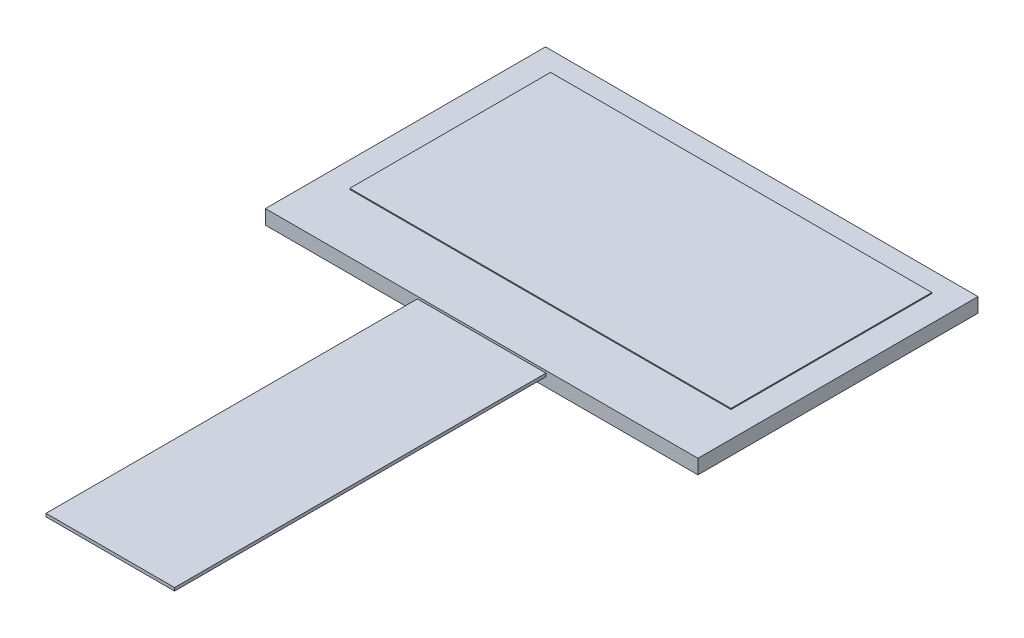
SolidWorks part; units mm, degrees
ref_plane "前视基准面" through (0, 0, 0) normal (0, 0, 1) x (1, 0, 0)
ref_plane "上视基准面" through (0, 0, 0) normal (0, 1, 0) x (1, 0, 0)
ref_plane "右视基准面" through (0, 0, 0) normal (1, 0, 0) x (0, 0, -1)
sketch "草图1" plane through (0, 0, 0) normal (0, 1, 0) x (1, 0, 0)
  line L1 (21.02, -13.61) -> (-21.02, -13.61)
  line L2 (21.02, -13.61) -> (21.02, 13.61)
  line L3 (21.02, 13.61) -> (-21.02, 13.61)
  line L4 (-21.02, -13.61) -> (-21.02, 13.61)
  line L5 (21.02, -13.61) -> (-21.02, 13.61) construction
  line L6 (21.02, 13.61) -> (-21.02, -13.61) construction
  point P0 (0, 0)
  dimension "D1" = 42.04
  dimension "D2" = 27.22
extrude "凸台-拉伸1" add sketch "草图1" along normal blind 1.4
sketch "草图2" plane through (0, 1.4, 0) normal (0, 1, 0) x (1, 0, 0)
  line L0 (-21.02, 13.61) -> (-21.02, -13.61) construction
  line L1 (-18.526, 11.61) -> (18.526, 11.61)
  line L2 (-18.526, 11.61) -> (-18.526, -7.906)
  line L3 (-18.526, -7.906) -> (18.526, -7.906)
  line L4 (18.526, 11.61) -> (18.526, -7.906)
  line L5 (21.02, 13.61) -> (-21.02, 13.61) construction
  dimension "D1" = 2.494
  dimension "D2" = 2
  dimension "D3" = 37.052
  dimension "D4" = 19.516
extrude "凸台-拉伸2" add sketch "草图2" along normal blind 0.1
sketch "草图3" plane through (0, 0, 13.61) normal (0, 0, 1) x (1, 0, 0)
  line L1 (-6.25, 1.1819) -> (6.25, 1.1819)
  line L2 (-6.25, 1.1819) -> (-6.25, 0.8819)
  line L3 (-6.25, 0.8819) -> (6.25, 0.8819)
  line L4 (6.25, 1.1819) -> (6.25, 0.8819)
  line L5 (21.02, 1.4) -> (21.02, 0) construction
  point P6 (21.02, 0.7)
  dimension "D1" = 14.77
  dimension "D2" = 12.5
  dimension "D3" = 0.3
extrude "凸台-拉伸3" add sketch "草图3" along normal blind 36.1
